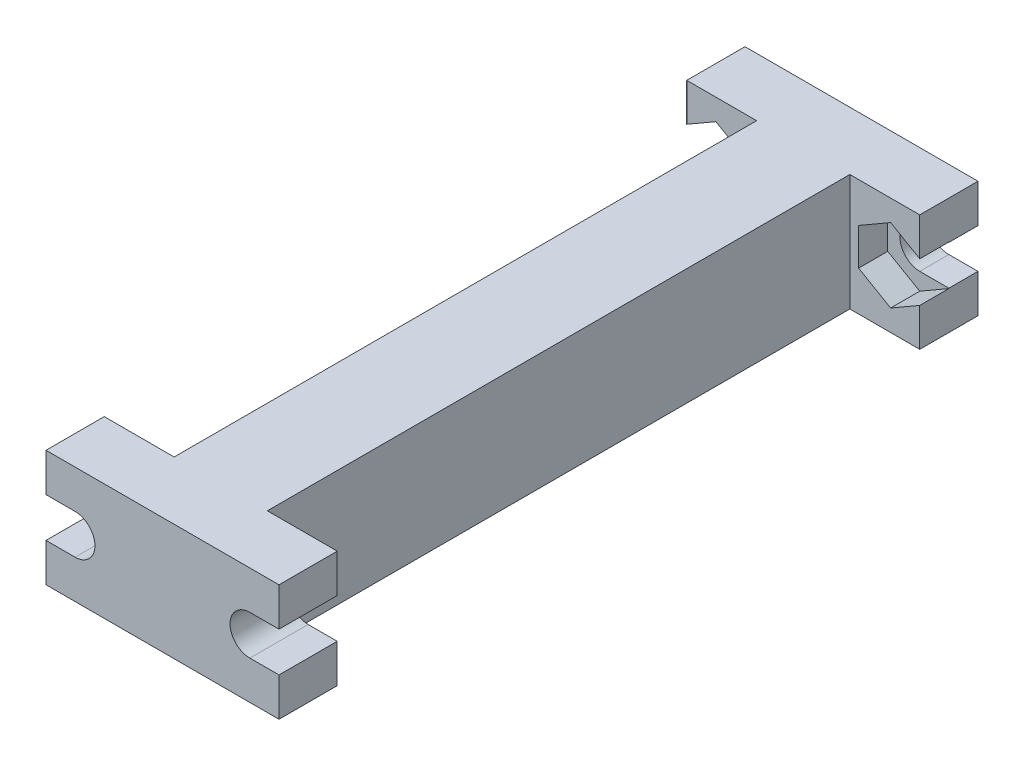
SolidWorks part; units mm, degrees
material "ABS"
ref_plane "Front" through (0, 0, 0) normal (0, 0, 1) x (1, 0, 0)
ref_plane "Top" through (0, 0, 0) normal (0, 1, 0) x (1, 0, 0)
ref_plane "Right" through (0, 0, 0) normal (1, 0, 0) x (0, 0, -1)
sketch "Sketch1" plane through (0, 0, 0) normal (0, 0, 1) x (1, 0, 0)
  line L1 (-10, -5) -> (10, -5)
  line L2 (-10, -5) -> (-10, 5)
  line L3 (-10, 5) -> (10, 5)
  line L4 (10, -5) -> (10, 5)
  line L5 (-10, -5) -> (10, 5) construction
  line L6 (-10, 5) -> (10, -5) construction
  point P0 (0, 0)
  dimension "D1" = 20
  dimension "D2" = 10
extrude "Boss-Extrude1" add sketch "Sketch1" along normal blind 5
sketch "Sketch2" plane through (0, 0, 5) normal (0, 0, 1) x (1, 0, 0)
  line L0 (10, 5) -> (-10, 5) construction
  line L1 (-4, -5) -> (4, -5)
  line L3 (-4, 5) -> (4, 5)
  line L5 (-4, -5) -> (4, 5) construction
  line L6 (-4, 5) -> (4, -5) construction
  line L12 (-4, 5) -> (-4, -5)
  line L13 (4, 5) -> (4, -5)
  point P0 (0, 0)
  point P8 (0, 0)
  dimension "D2" = 8
extrude "Boss-Extrude2" add sketch "Sketch2" along normal blind 50
sketch "Sketch3" plane through (0, 0, 5) normal (0, 0, 1) x (1, 0, 0)
  line L0 (-7.5, 0) -> (7.5, 0) construction
  line L5 (-7.5, 1.7) -> (-10, 1.7)
  line L6 (-10, 5) -> (-10, -5) construction
  line L7 (-10, 1.7) -> (-10, -1.7)
  line L8 (-10, -1.7) -> (-7.5, -1.7)
  line L9 (7.5, 1.7) -> (10, 1.7)
  line L12 (10, 1.7) -> (10, -1.7)
  line L13 (10, -5) -> (10, 5) construction
  line L14 (10, -1.7) -> (7.5, -1.7)
  circle A0 centre (-7.5, 0) radius 1.7 construction
  circle A1 centre (7.5, 0) radius 1.7 construction
  arc A4 (-7.5, -1.7) -> (-7.5, 1.7) centre (-7.5, 0) ccw
  arc A5 (7.5, 1.7) -> (7.5, -1.7) centre (7.5, 0) ccw
  point P0 (0, 0)
  point P2 (0, 0)
  dimension "D1" = 3.4
  dimension "D2" = 3.4
  dimension "D3" = 15
extrude "Cut-Extrude1" cut sketch "Sketch3" against normal blind 10
sketch "Sketch4" plane through (0, 0, 55) normal (0, 0, 1) x (1, 0, 0)
  line L0 (-7.5, 1.7) -> (-10, 1.7)
  line L1 (10, -5) -> (-10, -5)
  line L2 (10, -5) -> (10, -1.7)
  line L3 (10, 5) -> (-10, 5)
  line L4 (-10, -5) -> (-10, -1.7)
  line L5 (10, -5) -> (-10, 5) construction
  line L6 (10, 5) -> (-10, -5) construction
  line L8 (-10, -1.7) -> (-7.5, -1.7)
  line L9 (7.5, 1.7) -> (10, 1.7)
  line L11 (10, -1.7) -> (7.5, -1.7)
  line L12 (10, 1.7) -> (10, 5)
  line L13 (-10, 1.7) -> (-10, 5)
  arc A1 (7.5, 1.7) -> (7.5, -1.7) centre (7.5, 0) ccw
  arc A2 (-7.5, -1.7) -> (-7.5, 1.7) centre (-7.5, 0) ccw
  point P0 (0, 0)
  dimension "D1" = 1.7
extrude "Boss-Extrude3" add sketch "Sketch4" along normal blind 5
sketch "Sketch5" plane through (0, 0, 5) normal (0, 0, 1) x (1, 0, 0)
  line L0 (-4.75, 1.5877) -> (-4.75, -1.5877)
  line L1 (-4.75, 1.5877) -> (-7.5, 3.1754)
  line L2 (-7.5, 3.1754) -> (-10.25, 1.5877)
  line L3 (-10.25, 1.5877) -> (-10.25, -1.5877)
  line L4 (-10.25, -1.5877) -> (-7.5, -3.1754)
  line L5 (-7.5, -3.1754) -> (-4.75, -1.5877)
  circle A0 centre (-7.5, 0) radius 2.75 construction
  circle A1 centre (-7.5, 0) radius 3.1754 construction
  point P5 (-4.75, 0)
  point P8 (-10.25, 0)
  point P11 (-8.875, -2.3816)
  point P12 (-6.125, 2.3816)
  dimension "D1" = 5.5
extrude "Cut-Extrude2" cut sketch "Sketch5" against normal blind 2.5
mirror "Mirror1" about plane through (0, 0, 0) normal (1, 0, 0) of "Cut-Extrude2"
